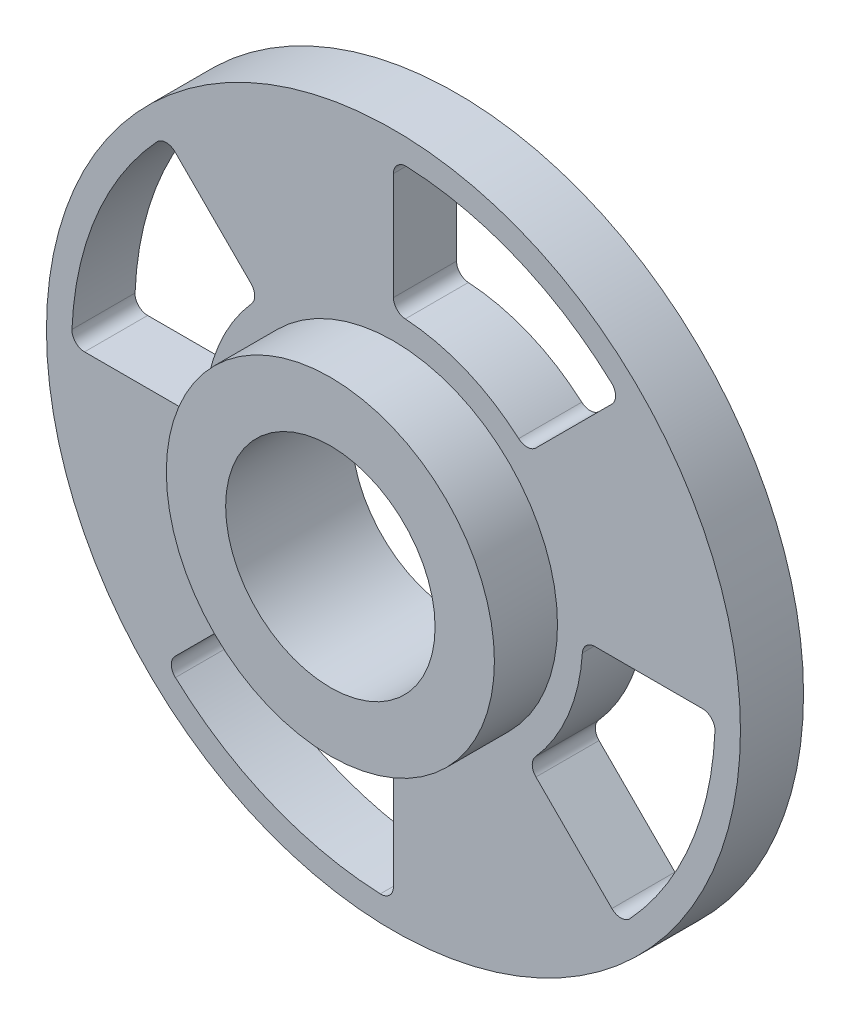
SolidWorks part; units mm, degrees
ref_plane "Front Plane" through (0, 0, 0) normal (0, 0, 1) x (1, 0, 0)
ref_plane "Top Plane" through (0, 0, 0) normal (0, 1, 0) x (1, 0, 0)
ref_plane "Right Plane" through (0, 0, 0) normal (1, 0, 0) x (0, 0, -1)
sketch "Sketch1" plane through (0, 0, 0) normal (0, 0, 1) x (1, 0, 0)
  circle A0 centre (0, 0) radius 4.15
  circle A1 centre (0, 0) radius 13.75
  dimension "D1" = 27.5
  dimension "D2" = 8.3
extrude "Boss-Extrude1" add sketch "Sketch1" along normal blind 2.5
sketch "Sketch2" plane through (0, 0, 2.5) normal (0, 0, 1) x (1, 0, 0)
  circle A0 centre (0, 0) radius 4.15
  circle A1 centre (0, 0) radius 6.5
  circle A2 centre (0, 0) radius 4.15 construction
  circle A3 centre (0, 0) radius 4 construction
  dimension "D1" = 8
  dimension "D2" = 2.5
extrude "Boss-Extrude2" add sketch "Sketch2" along normal blind 2.5
sketch "Sketch5" plane through (0, 0, 0) normal (0, 0, 1) x (1, 0, 0)
  line L0 (0, 0) -> (0, 7.5) construction
  line L1 (0, 7.5) -> (0, 12.75)
  line L2 (0, 0) -> (5.3033, 5.3033) construction
  line L3 (5.3033, 5.3033) -> (9.0156, 9.0156)
  circle A0 centre (0, 0) radius 12.75
  circle A1 centre (0, 0) radius 7.5
  circle A2 centre (0, 0) radius 13.75 construction
  circle A3 centre (0, 0) radius 6.5 construction
  dimension "D1" = 1
  dimension "D2" = 1
  dimension "D3" = 45
extrude "Cut-Extrude1" cut sketch "Sketch5" along normal through all contours A1 L3 A0 L1
fillet "Fillet1" radius 0.5 4 edges at (5.3033, 5.3033, 1.25) (9.0156, 9.0156, 1.25) (0, 7.5, 1.25) (0, 12.75, 1.25)
pattern_circular "CirPattern1" count 4 over 360 about axis through (0, 0, 0) along (0, 0, 1) of "Cut-Extrude1", "Fillet1"
